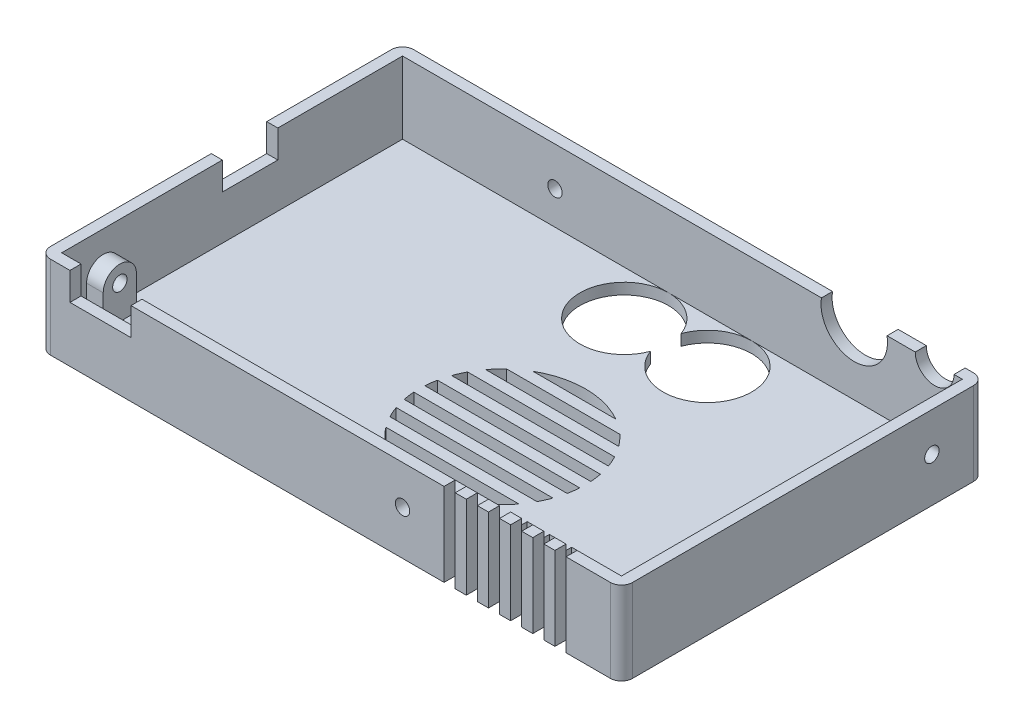
SolidWorks part; units mm, degrees
ref_plane "前视基准面" through (0, 0, 0) normal (0, 0, 1) x (1, 0, 0)
ref_plane "上视基准面" through (0, 0, 0) normal (0, 1, 0) x (1, 0, 0)
ref_plane "右视基准面" through (0, 0, 0) normal (1, 0, 0) x (0, 0, -1)
sketch "草图1" plane through (0, 0, 0) normal (0, 1, 0) x (1, 0, 0)
  line L1 (-52.5, 32.75) -> (52.5, 32.75)
  line L2 (-52.5, 32.75) -> (-52.5, -32.75)
  line L3 (-52.5, -32.75) -> (52.5, -32.75)
  line L4 (52.5, 32.75) -> (52.5, -32.75)
  dimension "D1" = 65.5
  dimension "D2" = 105
  dimension "D3" = 52.5
  dimension "D4" = 32.75
extrude "凸台-拉伸1" add sketch "草图1" along normal blind 15
shell "抽壳1" thickness 2
fillet "圆角1" radius 2 4 edges at (-52.5, 7.5, -32.75) (-52.5, 7.5, 32.75) (52.5, 7.5, 32.75) (52.5, 7.5, -32.75)
sketch "草图2" plane through (-52.5, 0, 0) normal (-1, 0, 0) x (0, 0, 1)
  line L0 (-30.75, 15) -> (30.75, 15) construction
  line L1 (-8.25, 15) -> (1.75, 15)
  line L2 (-8.25, 15) -> (-8.25, 10)
  line L3 (-8.25, 10) -> (1.75, 10)
  line L4 (1.75, 15) -> (1.75, 10)
  dimension "D1" = 22.5
  dimension "D2" = 10
  dimension "D3" = 5
extrude "切除-拉伸1" cut sketch "草图2" against normal blind 14
sketch "草图3" plane through (0, 0, 32.75) normal (0, 0, 1) x (1, 0, 0)
  line L0 (-50.5, 15) -> (50.5, 15) construction
  line L1 (-47, 15) -> (-36, 15)
  line L2 (-47, 15) -> (-47, 10)
  line L3 (-47, 10) -> (-36, 10)
  line L4 (-36, 15) -> (-36, 10)
  line L5 (-50.5, 15) -> (-50.5, 0) construction
  dimension "D1" = 11
  dimension "D2" = 5
  dimension "D3" = 3.5
extrude "切除-拉伸2" cut sketch "草图3" against normal blind 14
sketch "草图5" plane through (0, 0, 32.75) normal (0, 0, 1) x (1, 0, 0)
  line L0 (-36, 15) -> (50.5, 15) construction
  line L1 (42.5, 15) -> (40.5, 15)
  line L2 (42.5, 15) -> (42.5, -2.6635)
  line L3 (42.5, -2.6635) -> (40.5, -2.6635)
  line L4 (40.5, 15) -> (40.5, -2.6635)
  line L5 (38.5, 15) -> (38.5, -2.6635)
  line L6 (38.5, 15) -> (36.5, 15)
  line L7 (36.5, 15) -> (36.5, -2.6635)
  line L8 (38.5, -2.6635) -> (36.5, -2.6635)
  line L9 (34.5, 15) -> (34.5, -2.6635)
  line L10 (34.5, 15) -> (32.5, 15)
  line L11 (32.5, 15) -> (32.5, -2.6635)
  line L12 (34.5, -2.6635) -> (32.5, -2.6635)
  line L13 (30.5, 15) -> (30.5, -2.6635)
  line L14 (30.5, 15) -> (28.5, 15)
  line L15 (28.5, 15) -> (28.5, -2.6635)
  line L16 (30.5, -2.6635) -> (28.5, -2.6635)
  line L17 (27.5, 18.5112) -> (27.5, -5.0383) construction
  line L18 (24.5, -2.6635) -> (26.5, -2.6635)
  line L19 (26.5, 15) -> (26.5, -2.6635)
  line L20 (24.5, 15) -> (26.5, 15)
  line L21 (24.5, 15) -> (24.5, -2.6635)
  line L22 (20.5, -2.6635) -> (22.5, -2.6635)
  line L23 (22.5, 15) -> (22.5, -2.6635)
  line L24 (20.5, 15) -> (22.5, 15)
  line L25 (20.5, 15) -> (20.5, -2.6635)
  dimension "D1" = 2
  dimension "D2" = 8
  dimension "D4" = 1
  dimension "D3" = 4
extrude "切除-拉伸3" cut sketch "草图5" against normal blind 15
sketch "草图6" plane through (0, 0, -32.75) normal (0, 0, -1) x (-1, 0, 0)
  line L4 (-50.5, 15) -> (50.5, 15) construction
  line L5 (-50.5, 15) -> (-50.5, 0) construction
  circle A0 centre (-45.5, 15) radius 3.5
  circle A1 centre (-31, 14) radius 6
  dimension "D1" = 5
  dimension "D2" = 7
  dimension "D4" = 12
  dimension "D3" = 1
  dimension "D5" = 19.5
extrude "切除-拉伸4" cut sketch "草图6" against normal blind 15
sketch "草图7" plane through (0, 2, 0) normal (0, 1, 0) x (1, 0, 0)
  line L0 (50.5, -30.75) -> (50.5, 30.75) construction
  line L1 (50.5, 30.75) -> (-50.5, 30.75) construction
  arc A0 (5, 19.9661) -> (5, 25.5339) centre (12.5, 22.75) ccw
  arc A1 (5, 25.5339) -> (5, 19.9661) centre (-2.5, 22.75) ccw
  dimension "D3" = 16
  dimension "D4" = 16
  dimension "D1" = 38
  dimension "D2" = 8
  dimension "D5" = 15
extrude "切除-拉伸5" cut sketch "草图7" against normal blind 15
sketch "草图8" plane through (0, 0, 0) normal (0, -1, 0) x (1, 0, 0)
  line L0 (5, -25.5339) -> (5, 18.8075) construction
  line L1 (-50.5, 32.75) -> (20.5, 32.75) construction
  line L3 (-2.4833, 19.75) -> (12.4833, 19.75)
  line L5 (-5.198, 17.75) -> (15.198, 17.75)
  line L7 (-7, 15.75) -> (17, 15.75)
  line L9 (-8.2665, 13.75) -> (18.2665, 13.75)
  line L11 (-9.1421, 11.75) -> (19.1421, 11.75)
  line L13 (-9.6969, 9.75) -> (19.6969, 9.75)
  line L15 (-9.9666, 7.75) -> (19.9666, 7.75)
  line L17 (-9.9666, 5.75) -> (19.9666, 5.75)
  line L19 (-9.6969, 3.75) -> (19.6969, 3.75)
  line L21 (-9.1421, 1.75) -> (19.1421, 1.75)
  line L23 (-8.2665, -0.25) -> (18.2665, -0.25)
  line L25 (-7, -2.25) -> (17, -2.25)
  line L27 (-5.198, -4.25) -> (15.198, -4.25)
  line L29 (-2.4833, -6.25) -> (12.4833, -6.25)
  arc A0 (-5.198, 17.75) -> (-7, 15.75) centre (5, 6.75) ccw
  arc A1 (12.4833, 19.75) -> (-2.4833, 19.75) centre (5, 6.75) ccw
  arc A2 (-8.2665, 13.75) -> (-9.1421, 11.75) centre (5, 6.75) ccw
  arc A3 (17, 15.75) -> (15.198, 17.75) centre (5, 6.75) ccw
  arc A4 (-9.6969, 9.75) -> (-9.9666, 7.75) centre (5, 6.75) ccw
  arc A5 (19.1421, 11.75) -> (18.2665, 13.75) centre (5, 6.75) ccw
  arc A6 (19.9666, 7.75) -> (19.6969, 9.75) centre (5, 6.75) ccw
  arc A7 (-9.9666, 5.75) -> (-9.6969, 3.75) centre (5, 6.75) ccw
  arc A8 (19.6969, 3.75) -> (19.9666, 5.75) centre (5, 6.75) ccw
  arc A9 (-9.1421, 1.75) -> (-8.2665, -0.25) centre (5, 6.75) ccw
  arc A10 (18.2665, -0.25) -> (19.1421, 1.75) centre (5, 6.75) ccw
  arc A11 (-7, -2.25) -> (-5.198, -4.25) centre (5, 6.75) ccw
  arc A12 (-2.4833, -6.25) -> (12.4833, -6.25) centre (5, 6.75) ccw
  arc A13 (15.198, -4.25) -> (17, -2.25) centre (5, 6.75) ccw
  point P12 (5, 21.75)
  dimension "D2" = 30
  dimension "D1" = 26
  dimension "D4" = 7
extrude "切除-拉伸6" cut sketch "草图8" against normal blind 15
sketch "草图9" plane through (0, 2, 0) normal (0, 1, 0) x (1, 0, 0)
  line L0 (-50.5, -30.75) -> (20.5, -30.75) construction
  line L1 (-50.5, 30.75) -> (-50.5, -30.75) construction
  circle A0 centre (-43, -26.75) radius 1.75
  circle A1 centre (-38, -26.75) radius 1.75
  dimension "D3" = 3.5
  dimension "D4" = 3.5
  dimension "D1" = 4
  dimension "D2" = 7.5
  dimension "D5" = 5
extrude "切除-拉伸7" cut sketch "草图9" against normal blind 15
sketch "草图10" plane through (-52.5, 0, 0) normal (-1, 0, 0) x (0, 0, 1)
  line L0 (1.75, 15) -> (30.75, 15) construction
  circle A0 centre (23.25, 8) radius 1.3
  dimension "D1" = 7
  dimension "D3" = 2.6
  dimension "D2" = 7.5
extrude "切除-拉伸8" cut sketch "草图10" against normal blind 15
sketch "草图12" plane through (52.5, 0, 0) normal (1, 0, 0) x (0, 0, -1)
  line L0 (30.75, 0) -> (30.75, 15) construction
  line L1 (-30.75, 15) -> (30.75, 15) construction
  circle A0 centre (23.25, 8) radius 1.3
  dimension "D1" = 7.5
  dimension "D2" = 7
extrude "切除-拉伸9" cut sketch "草图12" against normal blind 15
sketch "草图13" plane through (-50.5, 0, 0) normal (1, 0, 0) x (0, 0, -1)
  line L0 (30.75, 2) -> (-30.75, 2) construction
  line L2 (-26.25, 8) -> (-26.25, 2)
  line L3 (-26.25, 2) -> (-20.25, 2)
  line L4 (-20.25, 8) -> (-20.25, 2)
  arc A0 (-20.25, 8) -> (-26.25, 8) centre (-23.25, 8) ccw
  dimension "D1" = 3
extrude "凸台-拉伸3" add sketch "草图13" along normal blind 3
sketch "草图16" plane through (-50.5, 0, 0) normal (-1, 0, 0) x (0, 0, 1)
  circle A0 centre (23.25, 8) radius 1.3
extrude "切除-拉伸11" cut sketch "草图16" against normal blind 8
sketch "草图17" plane through (0, 0, 32.75) normal (0, 0, 1) x (1, 0, 0)
  line L1 (-36, 15) -> (20.5, 15) construction
  line L2 (52.5, 15) -> (52.5, 0) construction
  circle A0 centre (13, 8) radius 1.3
  dimension "D3" = 2.6
  dimension "D1" = 39.5
  dimension "D2" = 7
extrude "切除-拉伸12" cut sketch "草图17" against normal blind 39
sketch "草图18" plane through (0, 0, -32.75) normal (0, 0, -1) x (-1, 0, 0)
  line L0 (-25.0839, 15) -> (50.5, 15) construction
  line L2 (52.5, 15) -> (52.5, 0) construction
  circle A0 centre (23, 8) radius 1.3
  dimension "D1" = 2.6
  dimension "D2" = 7
  dimension "D3" = 29.5
extrude "切除-拉伸13" cut sketch "草图18" against normal blind 39
